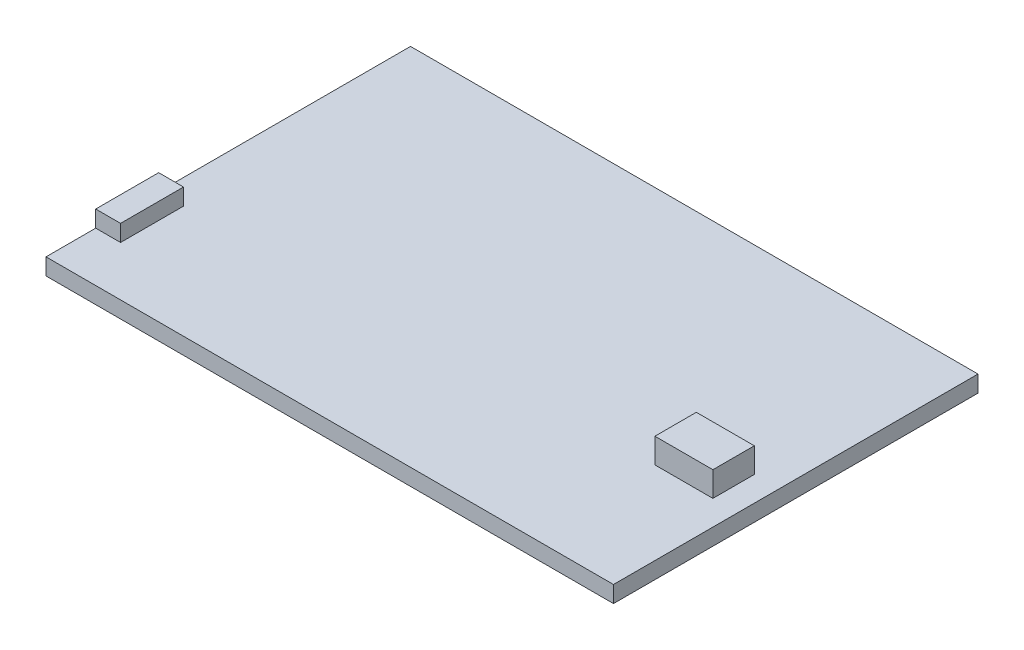
SolidWorks part; units mm, degrees
ref_plane "Front Plane" through (0, 0, 0) normal (0, 0, 1) x (1, 0, 0)
ref_plane "Top Plane" through (0, 0, 0) normal (0, 1, 0) x (1, 0, 0)
ref_plane "Right Plane" through (0, 0, 0) normal (1, 0, 0) x (0, 0, -1)
sketch "Sketch1" plane through (0, 0, 0) normal (0, 1, 0) x (1, 0, 0)
  line L1 (-34.25, -22) -> (34.25, -22)
  line L2 (-34.25, -22) -> (-34.25, 22)
  line L3 (-34.25, 22) -> (34.25, 22)
  line L4 (34.25, -22) -> (34.25, 22)
  line L5 (-34.25, -22) -> (34.25, 22) construction
  line L6 (-34.25, 22) -> (34.25, -22) construction
  point P0 (0, 0)
  dimension "D1" = 68.5
  dimension "D2" = 44
extrude "Boss-Extrude1" add sketch "Sketch1" along normal blind 2
sketch "Sketch2" plane through (0, 2, 0) normal (0, 1, 0) x (1, 0, 0)
  line L0 (34.25, -22) -> (34.25, 22) construction
  line L1 (31.25, -2) -> (24.25, -2)
  line L2 (31.25, -2) -> (31.25, -7)
  line L3 (31.25, -7) -> (24.25, -7)
  line L4 (24.25, -2) -> (24.25, -7)
  line L6 (-34.25, -22) -> (34.25, -22) construction
  dimension "D1" = 3
  dimension "D2" = 15
  dimension "D3" = 5
  dimension "D4" = 7
extrude "Boss-Extrude2" add sketch "Sketch2" along normal blind 3
sketch "Sketch3" plane through (0, 2, 0) normal (0, 1, 0) x (1, 0, 0)
  line L0 (-34.25, 22) -> (-34.25, -22) construction
  line L1 (-34.25, -16) -> (-31.25, -16)
  line L2 (-34.25, -16) -> (-34.25, -8.4)
  line L3 (-34.25, -8.4) -> (-31.25, -8.4)
  line L4 (-31.25, -16) -> (-31.25, -8.4)
  line L5 (-34.25, -22) -> (34.25, -22) construction
  dimension "D1" = 6
  dimension "D2" = 7.6
  dimension "D3" = 3
extrude "Boss-Extrude3" add sketch "Sketch3" along normal blind 2
